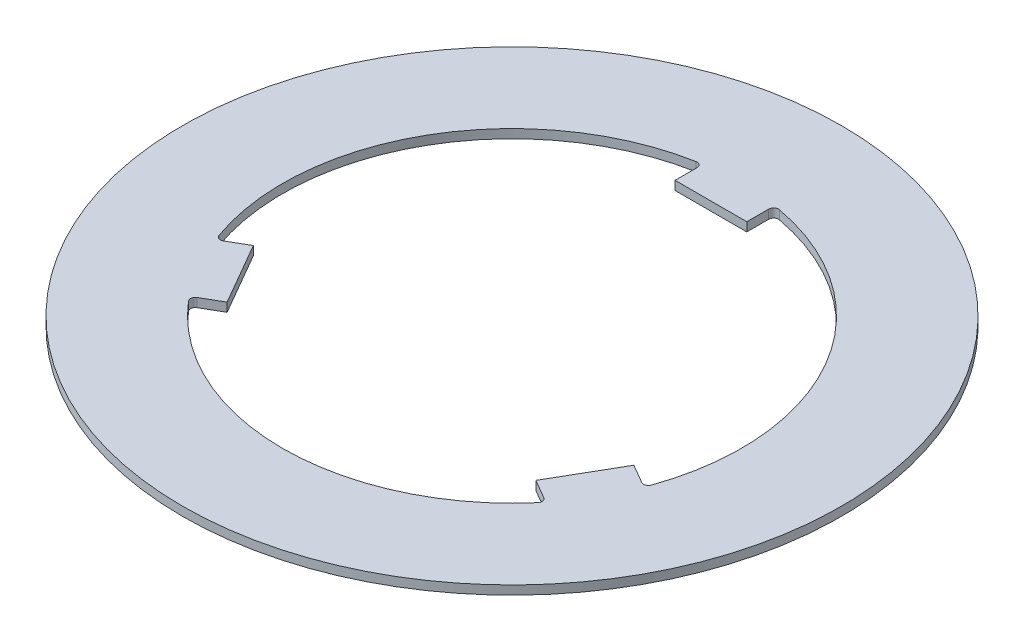
SolidWorks part; units mm, degrees
material "1.0060 (E335)"
ref_plane "Front Plane" through (0, 0, 0) normal (0, 0, 1) x (1, 0, 0)
ref_plane "Top Plane" through (0, 0, 0) normal (0, 1, 0) x (1, 0, 0)
ref_plane "Right Plane" through (0, 0, 0) normal (1, 0, 0) x (0, 0, -1)
sketch "Sketch1" plane through (0, 0, 0) normal (0, 1, 0) x (1, 0, 0)
  circle A0 centre (0, 0) radius 54
  circle A1 centre (0, 0) radius 37.6
  dimension "D1" = 108
  dimension "D2" = 75.2
extrude "Boss-Extrude1" add sketch "Sketch1" along normal mid plane 1.45
sketch "Sketch2" plane through (0, 0, 0) normal (0, 1, 0) x (1, 0, 0)
  line L0 (0, -1000) -> (0, 49000) construction
  line L1 (-5.875, 32.6) -> (5.875, 32.6)
  line L2 (5.875, 32.6) -> (5.875, 37.1382)
  line L3 (-5.875, 32.6) -> (-5.875, 37.1382)
  circle A0 centre (0, 0) radius 37.6 construction
  arc A1 (5.875, 37.1382) -> (-5.875, 37.1382) centre (0, 0) ccw
  point P5 (0, 32.6)
  dimension "D1" = 11.75
  dimension "D2" = 32.6
extrude "Boss-Extrude2" add sketch "Sketch2" along normal mid plane 1.45
fillet "Fillet1" radius 0.8 2 edges at (5.875, 0, -37.1382) (-5.875, 0, -37.1382)
pattern_circular "CirPattern1" count 3 over 360 about axis through (0, 0, 0) along (0, 1, 0) of "Boss-Extrude2", "Fillet1"
